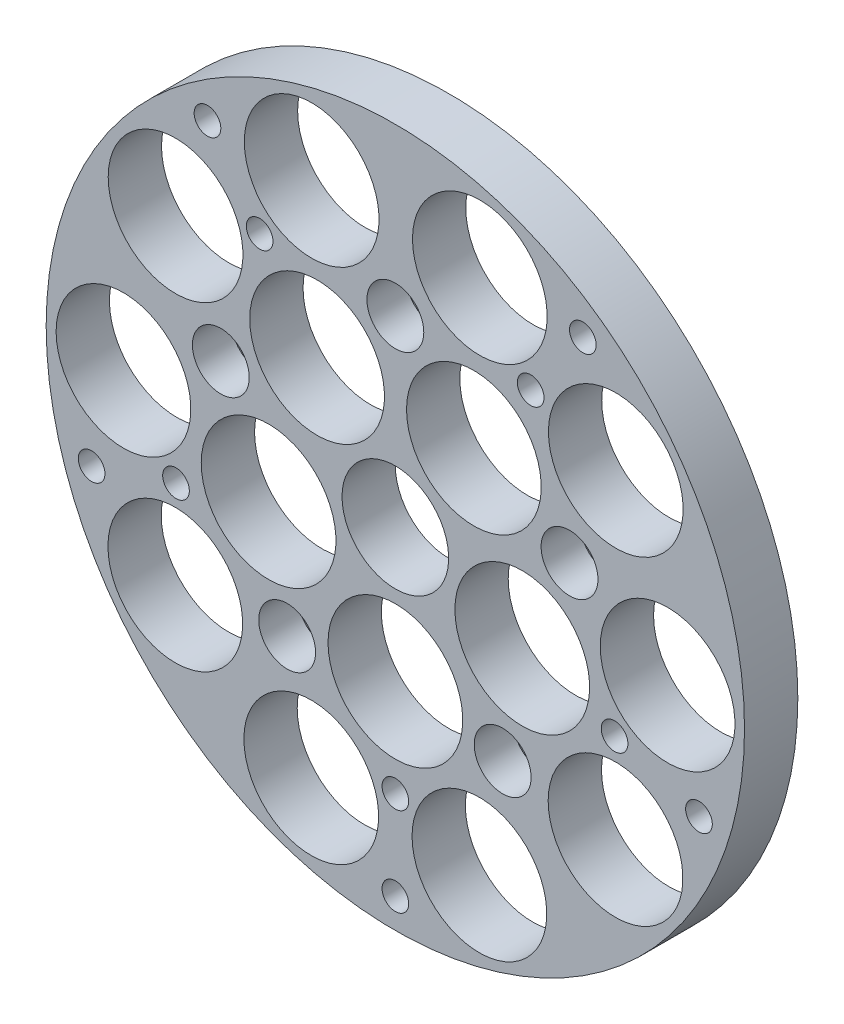
SolidWorks part; units mm, degrees
ref_plane "Front Plane" through (0, 0, 0) normal (0, 0, 1) x (1, 0, 0)
ref_plane "Top Plane" through (0, 0, 0) normal (0, 1, 0) x (1, 0, 0)
ref_plane "Right Plane" through (0, 0, 0) normal (1, 0, 0) x (0, 0, -1)
sketch "Sketch1" plane through (0, 0, 0) normal (0, 0, 1) x (1, 0, 0)
  line L0 (-24.8424, 29.885) -> (-20.6863, 32.8988)
  line L1 (-22.7643, 31.3919) -> (0, 0) construction
  line L2 (0, 0) -> (-50.8, 0) construction
  circle A0 centre (0, 0) radius 50.8
  circle A1 centre (0, 0) radius 38.862 construction
  circle A12 centre (0, 0) radius 19.05 construction
  circle A19 centre (-38.862, 0) radius 9.6266
  circle A20 centre (0, 0) radius 9.4234
  circle A22 centre (-31.416, 22.8522) radius 9.6266
  circle A23 centre (-11.9598, 36.9634) radius 9.6266
  circle A24 centre (12.0749, 36.9435) radius 9.6266
  circle A25 centre (31.5077, 22.8002) radius 9.6266
  circle A26 centre (38.9159, -0.0643) radius 9.6266
  circle A27 centre (31.4699, -22.9165) radius 9.6266
  circle A28 centre (12.0138, -37.0277) radius 9.6266
  circle A29 centre (-12.021, -37.0078) radius 9.6266
  circle A30 centre (-31.4538, -22.8645) radius 9.6266
  circle A31 centre (-11.1834, 15.4219) radius 9.6266
  circle A32 centre (11.2251, 15.4118) radius 9.6266
  circle A33 centre (18.1401, -5.9031) radius 9.6266
  circle A34 centre (0.0053, -19.0663) radius 9.6266
  circle A35 centre (-18.1176, -5.8868) radius 9.6266
  point P27 (0, 0)
  point P32 (0.027, -0.0321)
  point P43 (0, 0)
  point P49 (0.0139, -0.0045)
  dimension "D1" = 101.6
  dimension "D2" = 11.938
  dimension "D3" = 19.2532
  dimension "D4" = 38.1
  dimension "D5" = 10
  dimension "D6" = 5
  dimension "D7" = 19.2532
sketch "Sketch2" plane through (0, 0, 0) normal (0, 0, 1) x (1, 0, 0)
  circle A0 centre (0, 0) radius 49.911
  circle A1 centre (0.0053, -19.0663) radius 9.6266 construction
  circle A2 centre (18.1401, -5.9031) radius 9.6266 construction
  circle A3 centre (11.2251, 15.4118) radius 9.6266 construction
  circle A4 centre (-11.1834, 15.4219) radius 9.6266 construction
  circle A5 centre (-18.1176, -5.8868) radius 9.6266 construction
  circle A6 centre (-38.862, 0) radius 9.6266 construction
  circle A7 centre (-31.4538, -22.8645) radius 9.6266 construction
  circle A8 centre (-12.021, -37.0078) radius 9.6266 construction
  circle A9 centre (12.0138, -37.0277) radius 9.6266 construction
  circle A10 centre (31.4699, -22.9165) radius 9.6266 construction
  circle A11 centre (38.9159, -0.0643) radius 9.6266 construction
  circle A12 centre (31.5077, 22.8002) radius 9.6266 construction
  circle A13 centre (12.0749, 36.9435) radius 9.6266 construction
  circle A14 centre (-11.9598, 36.9634) radius 9.6266 construction
  circle A15 centre (-31.416, 22.8522) radius 9.6266 construction
  circle A17 centre (0, 0) radius 7.62
  circle A18 centre (0.0053, -19.0663) radius 9.6266
  circle A19 centre (18.1401, -5.9031) radius 9.6266
  circle A20 centre (11.2251, 15.4118) radius 9.6266
  circle A21 centre (-11.1834, 15.4219) radius 9.6266
  circle A22 centre (-18.1176, -5.8868) radius 9.6266
  circle A23 centre (-38.862, 0) radius 9.6266
  circle A24 centre (-31.4538, -22.8645) radius 9.6266
  circle A25 centre (-12.021, -37.0078) radius 9.6266
  circle A26 centre (12.0138, -37.0277) radius 9.6266
  circle A27 centre (31.4699, -22.9165) radius 9.6266
  circle A28 centre (38.9159, -0.0643) radius 9.6266
  circle A29 centre (31.5077, 22.8002) radius 9.6266
  circle A30 centre (12.0749, 36.9435) radius 9.6266
  circle A31 centre (-11.9598, 36.9634) radius 9.6266
  circle A32 centre (-31.416, 22.8522) radius 9.6266
  dimension "D1" = 15.24
  dimension "D2" = 99.822
extrude "Boss-Extrude3" add sketch "Sketch2" along normal blind 7.62
sketch "Sketch3" plane through (0, 0, 0) normal (0, 0, 1) x (1, 0, 0)
  line L0 (0, 0) -> (0, 50.8) construction
  line L1 (-12.7, 49.1869) -> (-12.7, 48.2682)
  line L2 (12.7, 49.1869) -> (12.7, 48.2682)
  line L3 (36.2471, 35.592) -> (35.4515, 35.1326)
  line L4 (48.9471, 13.5949) -> (48.1515, 13.1356)
  line L5 (48.9471, -13.5949) -> (48.1515, -13.1356)
  line L6 (36.2471, -35.592) -> (35.4515, -35.1326)
  line L7 (12.7, -49.1869) -> (12.7, -48.2682)
  line L8 (-12.7, -49.1869) -> (-12.7, -48.2682)
  line L9 (-36.2471, -35.592) -> (-35.4515, -35.1326)
  line L10 (-48.9471, -13.5949) -> (-48.1515, -13.1356)
  line L11 (-48.9471, 13.5949) -> (-48.1515, 13.1356)
  line L12 (-36.2471, 35.592) -> (-35.4515, 35.1326)
  arc A0 (12.7, 49.1869) -> (-12.7, 49.1869) centre (0, 0) ccw
  circle A1 centre (0, 0) radius 49.911 construction
  arc A2 (12.7, 48.2682) -> (-12.7, 48.2682) centre (0, 0) ccw
  arc A3 (48.9471, 13.5949) -> (36.2471, 35.592) centre (0, 0) ccw
  arc A4 (48.1515, 13.1356) -> (35.4515, 35.1326) centre (0, 0) ccw
  arc A5 (36.2471, -35.592) -> (48.9471, -13.5949) centre (0, 0) ccw
  arc A6 (35.4515, -35.1326) -> (48.1515, -13.1356) centre (0, 0) ccw
  arc A7 (-12.7, -49.1869) -> (12.7, -49.1869) centre (0, 0) ccw
  arc A8 (-12.7, -48.2682) -> (12.7, -48.2682) centre (0, 0) ccw
  arc A9 (-48.9471, -13.5949) -> (-36.2471, -35.592) centre (0, 0) ccw
  arc A10 (-48.1515, -13.1356) -> (-35.4515, -35.1326) centre (0, 0) ccw
  arc A11 (-36.2471, 35.592) -> (-48.9471, 13.5949) centre (0, 0) ccw
  arc A12 (-35.4515, 35.1326) -> (-48.1515, 13.1356) centre (0, 0) ccw
  point P3 (12.7, 49.1869)
  point P6 (-12.7, 49.1869)
  point P13 (48.9471, 13.5949)
  point P14 (36.2471, 35.592)
  point P19 (36.2471, -35.592)
  point P20 (48.9471, -13.5949)
  point P25 (-12.7, -49.1869)
  point P26 (12.7, -49.1869)
  point P31 (-48.9471, -13.5949)
  point P32 (-36.2471, -35.592)
  point P37 (-36.2471, 35.592)
  point P38 (-48.9471, 13.5949)
  point P43 (0, 0)
  dimension "D1" = 101.6
  dimension "D2" = 12.7
extrude "Boss-Extrude4" [suppressed] add sketch "Sketch3" along normal blind 7.874
sketch "Sketch4" plane through (0, 0, 7.62) normal (0, 0, 1) x (1, 0, 0)
  line L0 (0, 0) -> (0, 50.8) construction
  line L1 (-11.9598, 27.3368) -> (-11.9598, 25.0171) construction
  line L2 (-11.9598, 26.177) -> (0, 26.177) construction
  circle A0 centre (0, 0) radius 50.8 construction
  circle A1 centre (-11.9598, 36.9634) radius 9.6266 construction
  circle A2 centre (-11.1834, 15.4219) radius 9.6266 construction
  circle A3 centre (0, 26.177) radius 4.064
  circle A4 centre (24.8958, 8.038) radius 4.064
  circle A5 centre (15.3378, -21.2445) radius 4.064
  circle A6 centre (-15.4651, -21.2032) radius 4.064
  circle A7 centre (-24.9444, 8.1049) radius 4.064
  point P24 (-0.0352, -0.0256)
  dimension "D1" = 8.128
  dimension "D2" = 5
extrude "Cut-Extrude1" cut sketch "Sketch4" against normal through all
sketch "Sketch5" plane through (0, 0, 0) normal (0, 0, -1) x (-1, 0, 0)
  line L0 (-0.0082, -28.6929) -> (-0.0015, -49.911) construction
  line L1 (2.6499, -39.302) -> (-2.6597, -39.302) construction
  circle A3 centre (-0.0053, -19.0663) radius 9.6266 construction
  circle A4 centre (0, 0) radius 49.911 construction
  circle A5 centre (-12.0138, -37.0277) radius 9.6266 construction
  circle A43 centre (-0.0029, -45.6438) radius 1.905
  circle A44 centre (-0.0029, -32.9601) radius 1.905
  circle A45 centre (11.1834, 15.4219) radius 9.6266 construction
  circle A46 centre (12.021, -37.0078) radius 9.6266 construction
  circle A48 centre (12.021, -37.0078) radius 9.6266
  circle A51 centre (-43.3981, -14.0928) radius 1.905
  circle A52 centre (-31.3353, -10.1734) radius 1.905
  circle A55 centre (-26.8013, 36.9283) radius 1.905
  circle A56 centre (-19.346, 26.667) radius 1.905
  circle A59 centre (26.8514, 36.9101) radius 1.905
  circle A60 centre (19.3962, 26.6488) radius 1.905
  circle A63 centre (43.4137, -14.1222) radius 1.905
  circle A64 centre (31.3509, -10.2028) radius 1.905
  circle A139 centre (26.8264, -36.9365) radius 1.905 [skipped]
  circle A140 centre (19.3712, -26.6752) radius 1.905 [skipped]
  circle A141 centre (-26.8263, -36.9183) radius 1.905 [skipped]
  circle A142 centre (-19.371, -26.657) radius 1.905 [skipped]
  circle A143 centre (-43.3886, 14.114) radius 1.905 [skipped]
  circle A144 centre (-31.3257, 10.1946) radius 1.905 [skipped]
  circle A145 centre (0.028, 45.6356) radius 1.905 [skipped]
  circle A146 centre (0.028, 32.952) radius 1.905 [skipped]
  circle A147 centre (43.4233, 14.0847) radius 1.905 [skipped]
  circle A148 centre (31.3604, 10.1652) radius 1.905 [skipped]
  point P13 (-0.0049, -39.302)
  point P32 (-31.3201, 10.1775)
  point P42 (-26.8227, -36.9167)
  point P62 (0.0126, -0.0041)
  point P70 (0.001, 32.9322)
  point P80 (-43.3985, 14.1021)
  point P107 (43.3991, 14.1002)
  point P118 (0.001, 45.6322)
  point P145 (31.3207, 10.1757)
  point P155 (26.8212, -36.9178)
  point P183 (19.3563, -26.6433)
  point P200 (-19.3579, -26.6421)
  point P227 (-31.3201, 10.1775)
  point P234 (-26.8227, -36.9167)
  point P241 (0.001, 32.9322)
  point P248 (-43.3985, 14.1021)
  point P255 (43.3991, 14.1002)
  point P262 (0.001, 45.6322)
  point P269 (31.3207, 10.1757)
  point P276 (26.8212, -36.9178)
  point P283 (19.3563, -26.6433)
  point P290 (-19.3579, -26.6421)
  point P297 (-31.3201, 10.1775)
  point P304 (-26.8227, -36.9167)
  point P311 (0.001, 32.9322)
  point P318 (-43.3985, 14.1021)
  point P325 (43.3991, 14.1002)
  point P332 (0.001, 45.6322)
  point P339 (31.3207, 10.1757)
  point P346 (26.8212, -36.9178)
  point P353 (19.3563, -26.6433)
  point P360 (-19.3579, -26.6421)
  point P367 (-31.3201, 10.1775)
  point P374 (-26.8227, -36.9167)
  point P381 (0.001, 32.9322)
  point P388 (-43.3985, 14.1021)
  point P395 (43.3991, 14.1002)
  point P402 (0.001, 45.6322)
  point P409 (31.3207, 10.1757)
  point P416 (26.8212, -36.9178)
  point P423 (19.3563, -26.6433)
  point P430 (-19.3579, -26.6421)
  point P444 (-26.8259, -36.9265)
  point P458 (-43.3901, 14.1082)
  point P465 (43.4263, 14.0805)
  point P472 (0.0282, 45.6322)
  point P486 (26.8296, -36.9437)
  dimension "D2" = 4.2672
  dimension "D1" = 3.81
  dimension "D3" = 39.302
  dimension "D4" = 5.3096
  dimension "D5" = 10
extrude "Cut-Extrude2" cut sketch "Sketch5" against normal through all
chamfer "Chamfer1" distance 2.032 angle 35 5 edges at (-20.8804, 8.1049, 0) (4.064, 26.177, 0) (28.9598, 8.038, 0) (19.4018, -21.2445, 0) (-11.4011, -21.2032, 0)
